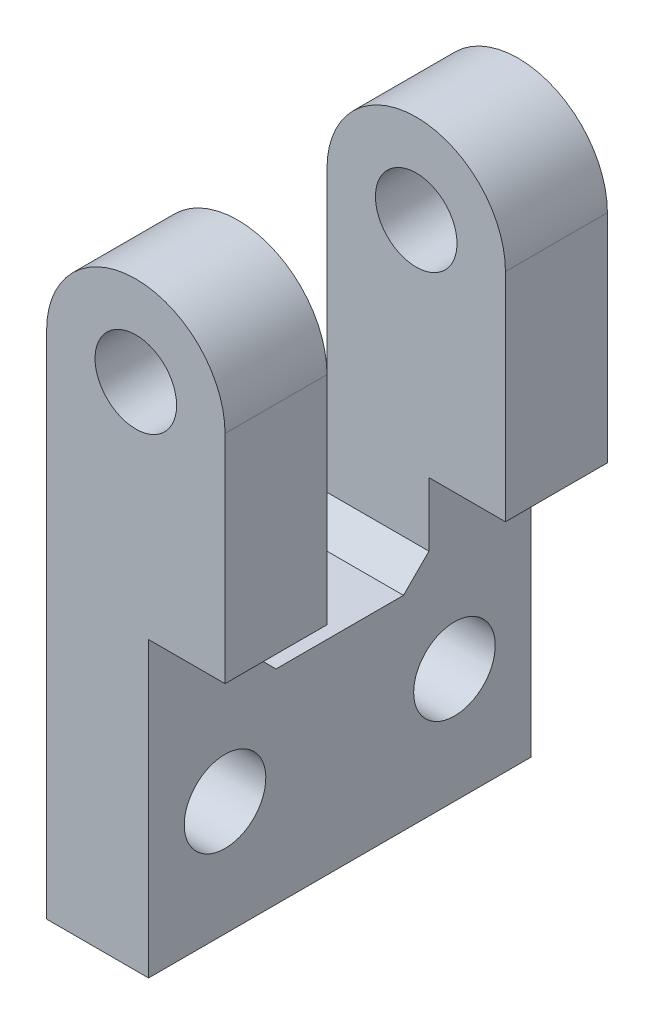
SolidWorks part; units mm, degrees
material "延性铁"
ref_plane "前视基准面" through (0, 0, 0) normal (0, 0, 1) x (1, 0, 0)
ref_plane "上视基准面" through (0, 0, 0) normal (0, 1, 0) x (1, 0, 0)
ref_plane "右视基准面" through (0, 0, 0) normal (1, 0, 0) x (0, 0, -1)
sketch "草图1" plane through (0, 0, 0) normal (0, 0, 1) x (1, 0, 0)
  line L0 (-3.5, -20) -> (-3.5, 0)
  line L3 (-3.5, -20) -> (3.5, -20)
  line L7 (3.5, -20) -> (3.5, 0)
  arc A0 (3.5, 0) -> (-3.5, 0) centre (0, 0) ccw
  circle A1 centre (0, 0) radius 1.6
  dimension "D2" = 7
  dimension "D1" = 20
  dimension "D3" = 3.5
  dimension "D4" = 3.5
extrude "凸台-拉伸1" add sketch "草图1" along normal blind 15
sketch "草图3" plane through (-3.5, 0, 0) normal (-1, 0, 0) x (0, 0, 1)
  line L0 (0, 0) -> (0, -20) construction
  line L1 (4, 6.8993) -> (11, 6.8993)
  line L2 (4, 6.8993) -> (4, -12)
  line L3 (4, -12) -> (11, -12)
  line L4 (11, 6.8993) -> (11, -12)
  line L5 (15, 0) -> (15, -20) construction
  line L8 (15, -20) -> (0, -20) construction
  dimension "D1" = 4
  dimension "D2" = 4
  dimension "D3" = 8
extrude "切除-拉伸2" cut sketch "草图3" against normal through all
sketch "草图4" plane through (0, 0, 0) normal (0, 0, -1) x (-1, 0, 0)
  line L0 (3.5, -20) -> (-3.5, -20) construction
  line L1 (-3.5, -25.5) -> (-0.5, -25.5)
  line L2 (-3.5, -25.5) -> (-3.5, -8.5)
  line L3 (-3.5, -8.5) -> (-0.5, -8.5)
  line L4 (-0.5, -25.5) -> (-0.5, -8.5)
  line L5 (-3.5, -25.5) -> (-0.5, -8.5) construction
  line L6 (-3.5, -8.5) -> (-0.5, -25.5) construction
  point P0 (-2, -17)
  dimension "D1" = 3
  dimension "D2" = 3
extrude "切除-拉伸3" cut sketch "草图4" against normal through all
sketch "草图5" plane through (-3.5, 0, 0) normal (-1, 0, 0) x (0, 0, 1)
  line L0 (4, -8.5) -> (0, -8.5) construction
  line L2 (15, 0) -> (15, -20) construction
  line L3 (0, 0) -> (0, -20) construction
  circle A0 centre (12, -15.5) radius 1.6
  circle A1 centre (3, -15.5) radius 1.6
  dimension "D1" = 7
  dimension "D2" = 0
  dimension "D3" = 3
  dimension "D4" = 3
extrude "切除-拉伸4" cut sketch "草图5" against normal blind 10
chamfer "倒角1" distance 1 angle 45 2 edges at (-1.5, -12, 11) (-1.5, -12, 4)
